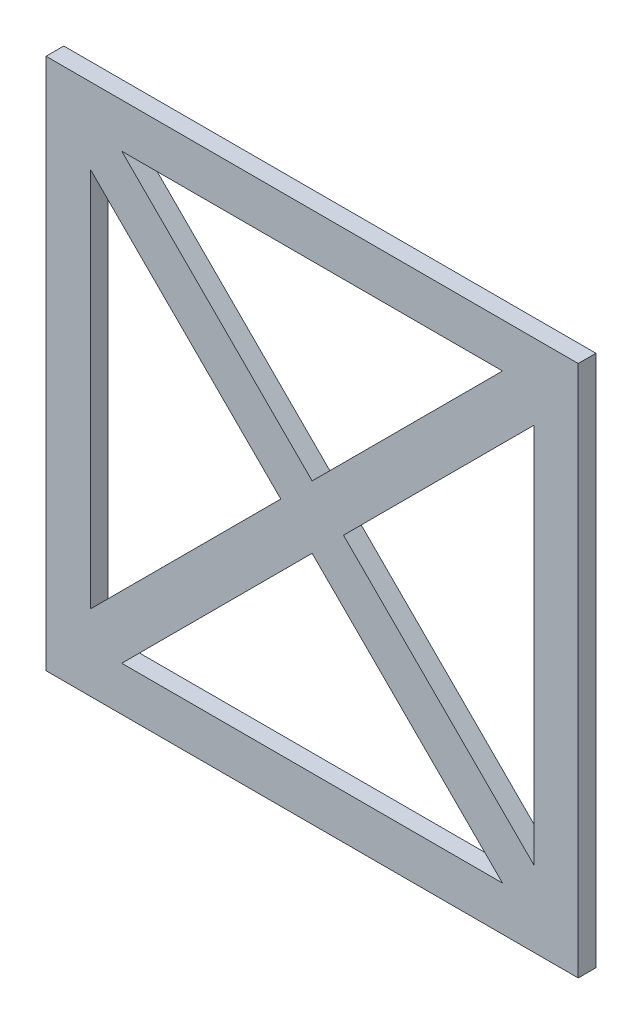
SolidWorks part; units mm, degrees
ref_plane "Front Plane" through (0, 0, 0) normal (0, 0, 1) x (1, 0, 0)
ref_plane "Top Plane" through (0, 0, 0) normal (0, 1, 0) x (1, 0, 0)
ref_plane "Right Plane" through (0, 0, 0) normal (1, 0, 0) x (0, 0, -1)
sketch "Sketch1" plane through (0, 0, 0) normal (0, 0, 1) x (1, 0, 0)
  line L5 (-107.3223, 125) -> (107.3223, 125)
  line L6 (-150, -150) -> (150, -150)
  line L18 (-150, -150) -> (-150, 150)
  line L19 (-150, 150) -> (150, 150)
  line L20 (150, -150) -> (150, 150)
  line L21 (-150, -150) -> (150, 150) construction
  line L22 (-150, 150) -> (150, -150) construction
  line L23 (125, -107.3223) -> (125, 107.3223)
  line L24 (-107.3223, -125) -> (107.3223, -125)
  line L25 (-125, -107.3223) -> (-125, 107.3223)
  line L26 (-125, 125) -> (0, 0) construction
  line L27 (125, 125) -> (0, 0) construction
  line L28 (107.3223, 125) -> (0, 17.6777)
  line L29 (-125, 107.3223) -> (-17.6777, 0)
  line L30 (125, 107.3223) -> (17.6777, 0)
  line L31 (-107.3223, 125) -> (0, 17.6777)
  line L32 (-17.6777, 0) -> (-125, -107.3223)
  line L33 (-116.1612, 133.8388) -> (133.8388, -116.1612) construction
  line L34 (-133.8388, 116.1612) -> (116.1612, -133.8388) construction
  line L35 (116.1612, 133.8388) -> (-133.8388, -116.1612) construction
  line L36 (125, -125) -> (125, 125) construction
  line L37 (133.8388, 116.1612) -> (-116.1612, -133.8388) construction
  line L38 (-125, 125) -> (125, 125) construction
  line L39 (-125, -125) -> (-125, 125) construction
  line L40 (17.6777, 0) -> (125, -107.3223)
  line L41 (0, -17.6777) -> (107.3223, -125)
  line L42 (0, -17.6777) -> (-107.3223, -125)
  line L44 (125, 125) -> (-125, -125) construction
  line L45 (-125, 125) -> (125, -125) construction
  line L46 (-125, -125) -> (125, -125) construction
  point P0 (0, 0)
  point P23 (0, 0)
  dimension "D1" = 300
  dimension "D2" = 300
  dimension "D3" = 25
  dimension "D4" = 12.5
  dimension "D5" = 12.5
extrude "Boss-Extrude1" add sketch "Sketch1" along normal blind 10
